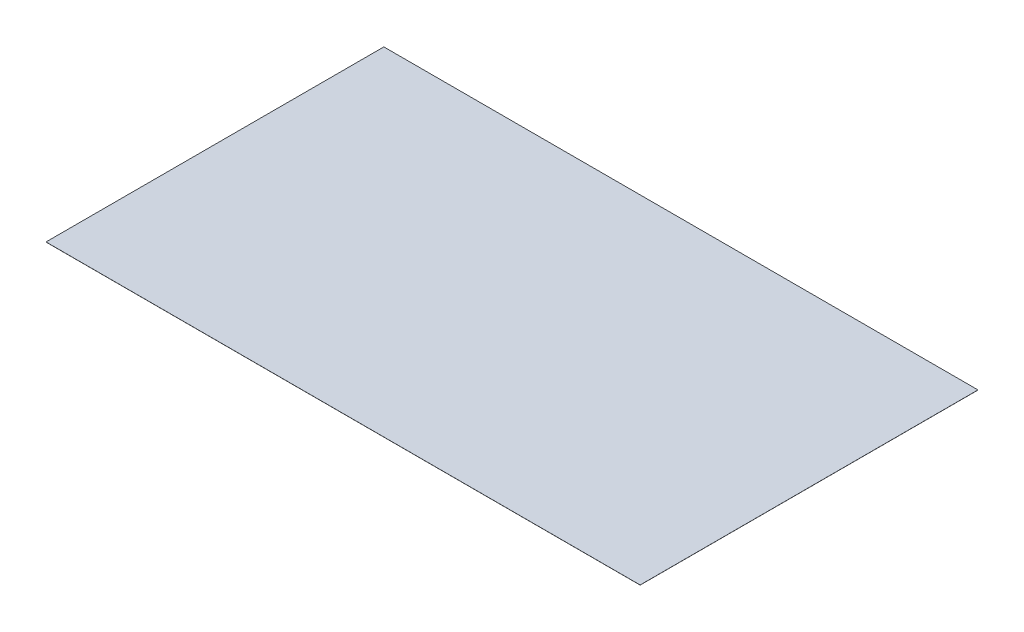
SolidWorks part; units mm, degrees
material "AISI 1020"
ref_plane "Спереди" through (0, 0, 0) normal (0, 0, 1) x (1, 0, 0)
ref_plane "Сверху" through (0, 0, 0) normal (0, 1, 0) x (1, 0, 0)
ref_plane "Справа" through (0, 0, 0) normal (1, 0, 0) x (0, 0, -1)
sketch "Эскиз1" plane through (0, 0, 0) normal (0, 1, 0) x (1, 0, 0)
  line L0 (-5100, 0) -> (-5100, -4120.283) construction
  line L1 (0, 0) -> (-5100, 0)
  line L2 (0, 0) -> (0, -2900)
  line L3 (0, -2900) -> (-5100, -2900)
  line L4 (-5100, 0) -> (-5100, -2900)
  line L5 (50, -2900) -> (-4100, -2900) construction
extrude "Бобышка-Вытянуть1" add sketch "Эскиз1" along normal blind 1
